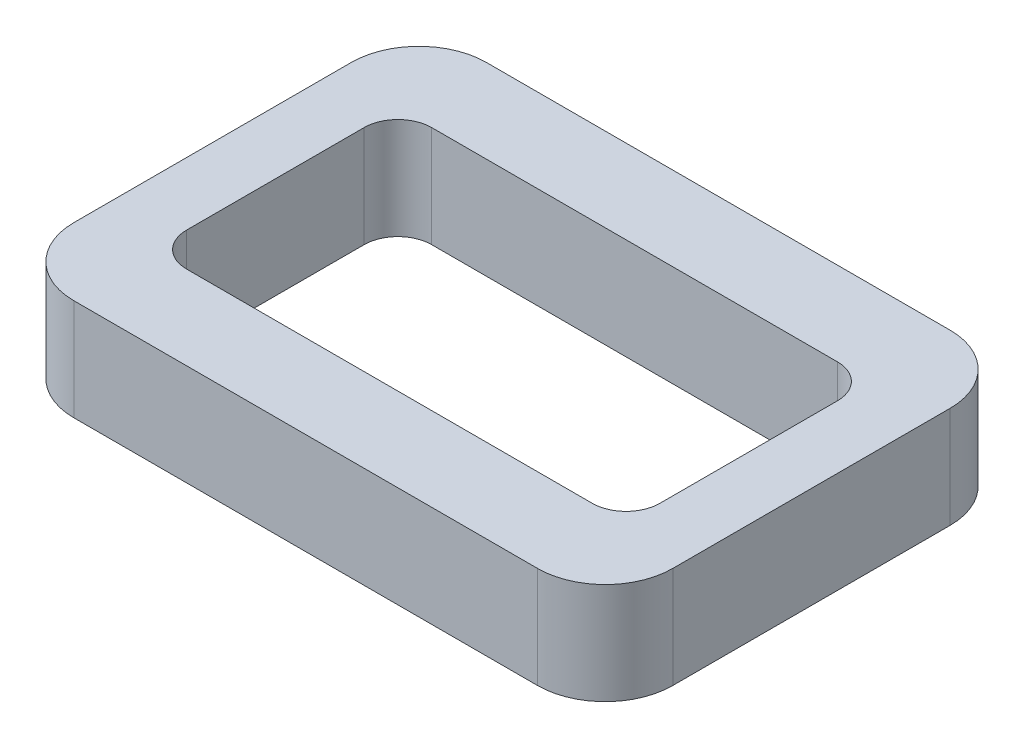
SolidWorks part; units mm, degrees
material "ABS"
ref_plane "Front Plane" through (0, 0, 0) normal (0, 0, 1) x (1, 0, 0)
ref_plane "Top Plane" through (0, 0, 0) normal (0, 1, 0) x (1, 0, 0)
ref_plane "Right Plane" through (0, 0, 0) normal (1, 0, 0) x (0, 0, -1)
sketch "Sketch2" plane through (0, 0, 0) normal (0, 1, 0) x (1, 0, 0)
  line L0 (41.9548, -23.6119) -> (52.1148, -23.6119) construction
  line L1 (12.3798, 24.2181) -> (40.6848, 24.2181) construction
  line L2 (11.1098, 22.9481) -> (11.1098, 22.3881) construction
  line L3 (12.3798, 21.1181) -> (40.6848, 21.1181) construction
  line L4 (82.9598, 22.9481) -> (82.9598, 22.3881)
  line L5 (82.9598, -23.8919) -> (82.9598, -23.3319)
  line L14 (41.9548, 22.9481) -> (41.9548, 22.3881) construction
  line L15 (52.1148, 22.9481) -> (52.1148, 22.3881)
  line L16 (53.3848, 24.2181) -> (81.6898, 24.2181)
  line L17 (53.3848, 21.1181) -> (81.6898, 21.1181)
  line L18 (53.3848, -22.0619) -> (81.6898, -22.0619)
  line L19 (53.3848, -25.1619) -> (81.6898, -25.1619)
  line L20 (52.1148, -23.8919) -> (52.1148, -23.3319)
  line L21 (41.9548, -23.8919) -> (41.9548, -23.3319)
  line L22 (12.3798, -22.0619) -> (40.6848, -22.0619)
  line L23 (11.1098, -23.8919) -> (11.1098, -23.3319)
  line L24 (12.3798, -25.1619) -> (40.6848, -25.1619)
  line L25 (41.9548, 22.6681) -> (52.1148, 22.6681) construction
  line L26 (47.0348, 22.6681) -> (47.0348, -23.6119) construction
  line L27 (11.1098, -23.6119) -> (41.9548, -23.6119) construction
  line L28 (81.8748, 30.5281) -> (12.1948, 30.5281)
  line L29 (92.0348, 20.3681) -> (92.0348, -21.3119)
  line L30 (81.8748, -31.4719) -> (12.1948, -31.4719)
  line L31 (2.0348, 20.3681) -> (2.0348, -21.3119)
  line L32 (92.0348, 30.5281) -> (2.0348, -31.4719) construction
  line L33 (92.0348, -31.4719) -> (2.0348, 30.5281) construction
  line L34 (16.5548, 17.9431) -> (77.5148, 17.9431)
  line L35 (11.4748, 12.8631) -> (11.4748, -13.8069)
  line L36 (16.5548, -18.8869) -> (77.5148, -18.8869)
  line L37 (82.5948, 12.8631) -> (82.5948, -13.8069)
  line L38 (11.4748, 17.9431) -> (82.5948, -18.8869) construction
  line L39 (11.4748, -18.8869) -> (82.5948, 17.9431) construction
  line L40 (52.1148, -23.6119) -> (82.9598, -23.6119) construction
  line L41 (26.5323, -25.1619) -> (26.5323, -22.0619) construction
  line L42 (67.5373, -25.1619) -> (67.5373, -22.0619) construction
  line L43 (11.4748, -0.4719) -> (82.5948, -0.4719) construction
  line L44 (11.1098, 22.6681) -> (41.9548, 22.6681) construction
  line L45 (26.5323, 24.2181) -> (26.5323, 21.1181) construction
  line L46 (52.1148, 22.6681) -> (82.9598, 22.6681) construction
  line L47 (67.5373, 24.2181) -> (67.5373, 21.1181) construction
  arc A0 (11.1098, 22.9481) -> (12.3798, 24.2181) centre (12.3798, 22.9481) cw construction
  arc A6 (11.1098, 22.3881) -> (12.3798, 21.1181) centre (12.3798, 22.3881) ccw construction
  arc A7 (82.9598, 22.9481) -> (81.6898, 24.2181) centre (81.6898, 22.9481) ccw
  arc A8 (81.6898, 21.1181) -> (82.9598, 22.3881) centre (81.6898, 22.3881) ccw
  arc A9 (40.6848, 24.2181) -> (41.9548, 22.9481) centre (40.6848, 22.9481) cw construction
  arc A10 (41.9548, 22.3881) -> (40.6848, 21.1181) centre (40.6848, 22.3881) cw construction
  arc A19 (52.1148, 22.3881) -> (53.3848, 21.1181) centre (53.3848, 22.3881) ccw
  arc A20 (52.1148, 22.9481) -> (53.3848, 24.2181) centre (53.3848, 22.9481) cw
  arc A21 (82.9598, -23.8919) -> (81.6898, -25.1619) centre (81.6898, -23.8919) cw
  arc A22 (81.6898, -22.0619) -> (82.9598, -23.3319) centre (81.6898, -23.3319) cw
  arc A23 (52.1148, -23.3319) -> (53.3848, -22.0619) centre (53.3848, -23.3319) cw
  arc A24 (52.1148, -23.8919) -> (53.3848, -25.1619) centre (53.3848, -23.8919) ccw
  arc A25 (40.6848, -25.1619) -> (41.9548, -23.8919) centre (40.6848, -23.8919) ccw
  arc A26 (41.9548, -23.3319) -> (40.6848, -22.0619) centre (40.6848, -23.3319) ccw
  arc A27 (11.1098, -23.3319) -> (12.3798, -22.0619) centre (12.3798, -23.3319) cw
  arc A28 (11.1098, -23.8919) -> (12.3798, -25.1619) centre (12.3798, -23.8919) ccw
  arc A29 (2.0348, 20.3681) -> (12.1948, 30.5281) centre (12.1948, 20.3681) cw
  arc A30 (12.1948, -31.4719) -> (2.0348, -21.3119) centre (12.1948, -21.3119) cw
  arc A31 (92.0348, -21.3119) -> (81.8748, -31.4719) centre (81.8748, -21.3119) cw
  arc A32 (92.0348, 20.3681) -> (81.8748, 30.5281) centre (81.8748, 20.3681) ccw
  arc A33 (11.4748, 12.8631) -> (16.5548, 17.9431) centre (16.5548, 12.8631) cw
  arc A34 (16.5548, -18.8869) -> (11.4748, -13.8069) centre (16.5548, -13.8069) cw
  arc A35 (82.5948, -13.8069) -> (77.5148, -18.8869) centre (77.5148, -13.8069) cw
  arc A36 (77.5148, 17.9431) -> (82.5948, 12.8631) centre (77.5148, 12.8631) cw
  circle A37 centre (67.5373, 22.6681) radius 1.65 construction
  circle A38 centre (26.5323, 22.6681) radius 1.65 construction
  circle A39 centre (26.5323, -23.6119) radius 1.65 construction
  circle A40 centre (67.5373, -23.6119) radius 1.65 construction
  point P3 (41.9548, -23.6119)
  point P11 (47.0348, -0.4719)
  point P73 (47.0348, -0.4719)
  dimension "D5" = 10.16
  dimension "D7" = 28.305
  dimension "D9" = 28.305
  dimension "D11" = 90
  dimension "D21" = 1.27
  dimension "D22" = 1.27
  dimension "D23" = 1.27
  dimension "D24" = 1.27
  dimension "D25" = 1.27
  dimension "D26" = 1.27
  dimension "D27" = 1.27
  dimension "D28" = 1.27
  dimension "D12" = 10.16
  dimension "D13" = 10.16
  dimension "D14" = 10.16
  dimension "D15" = 10.16
  dimension "D18" = 5.08
  dimension "D20" = 5.08
  dimension "D29" = 5.08
  dimension "D30" = 5.08
  dimension "D31" = 3.3
  dimension "D32" = 3.3
  dimension "D3" = 43.18
  dimension "D4" = 10.16
  dimension "D6" = 28.305
  dimension "D8" = 28.305
  dimension "D10" = 62
  dimension "D16" = 36.83
  dimension "D17" = 71.12
  dimension "D19" = 3.1
extrude "Boss-Extrude1" add sketch "Sketch2" along normal blind 15.24 contours A32 L28 A29 L31 A30 L30 A31 L29 | A34 L36 A35 L37 A36 L34 A33 L35
